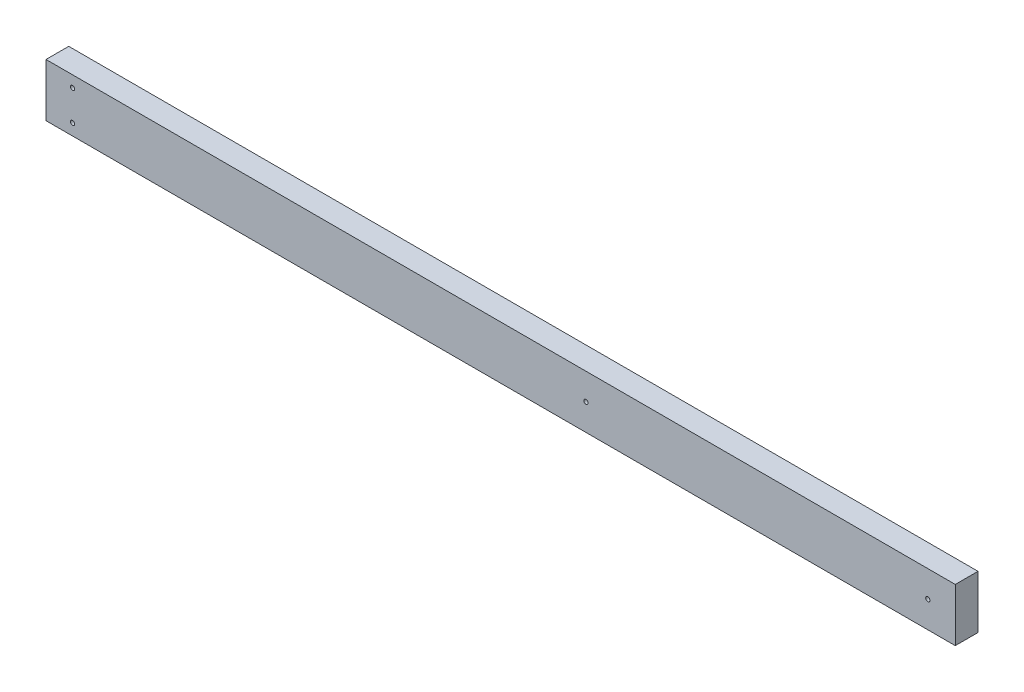
SolidWorks part; units mm, degrees
material "Pine"
ref_plane "Front Plane" through (0, 0, 0) normal (0, 0, 1) x (1, 0, 0)
ref_plane "Top Plane" through (0, 0, 0) normal (0, 1, 0) x (1, 0, 0)
ref_plane "Right Plane" through (0, 0, 0) normal (1, 0, 0) x (0, 0, -1)
sketch "Sketch1" plane through (0, 0, 0) normal (1, 0, 0) x (0, 0, -1)
  line L1 (0, 0) -> (38.1, 0)
  line L2 (0, 0) -> (0, 88.9)
  line L3 (0, 88.9) -> (38.1, 88.9)
  line L4 (38.1, 0) -> (38.1, 88.9)
  dimension "D1" = 38.1
  dimension "D2" = 88.9
extrude "Boss-Extrude1" add sketch "Sketch1" along normal blind 1524
sketch "Sketch2" plane through (0, 0, 0) normal (0, 0, 1) x (1, 0, 0)
  line L0 (0, 88.9) -> (0, 0) construction
  line L1 (1524, 0) -> (0, 0) construction
  line L2 (1524, 88.9) -> (0, 88.9) construction
  line L3 (1524, 88.9) -> (1524, 0) construction
  circle A0 centre (44.45, 19.05) radius 3.5719
  circle A1 centre (1477.9625, 44.45) radius 3.5719
  circle A2 centre (44.45, 69.85) radius 3.5719
  circle A3 centre (904.875, 44.45) radius 3.5719
  dimension "D2" = 7.1437
  dimension "D3" = 19.05
  dimension "D4" = 44.45
  dimension "D6" = 7.1437
  dimension "D9" = 7.1437
  dimension "D11" = 7.1437
  dimension "D12" = 619.125
  dimension "D1" = 44.45
  dimension "D5" = 46.0375
  dimension "D7" = 19.05
  dimension "D8" = 44.45
  dimension "D10" = 44.45
extrude "Cut-Extrude1" cut sketch "Sketch2" against normal through all
